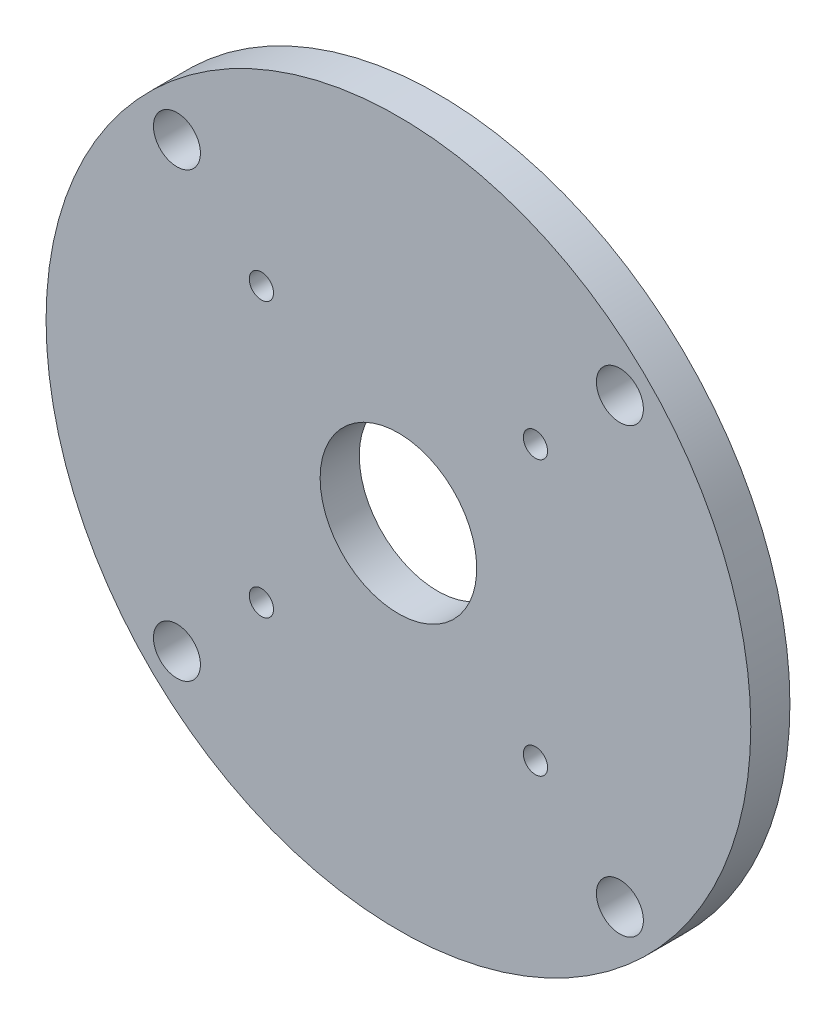
SolidWorks part; units mm, degrees
material "AISI 4130 Steel, normalized at 870C"
ref_plane "Front Plane" through (0, 0, 0) normal (0, 0, 1) x (1, 0, 0)
ref_plane "Top Plane" through (0, 0, 0) normal (0, 1, 0) x (1, 0, 0)
ref_plane "Right Plane" through (0, 0, 0) normal (1, 0, 0) x (0, 0, -1)
sketch "Sketch1" plane through (0, 0, 0) normal (0, 0, 1) x (1, 0, 0)
  line L1 (35.921, -35.921) -> (-35.921, -35.921) construction
  line L2 (35.921, -35.921) -> (35.921, 35.921) construction
  line L3 (35.921, 35.921) -> (-35.921, 35.921) construction
  line L4 (-35.921, -35.921) -> (-35.921, 35.921) construction
  line L5 (35.921, -35.921) -> (-35.921, 35.921) construction
  line L6 (35.921, 35.921) -> (-35.921, -35.921) construction
  circle A0 centre (0, 0) radius 50.8 construction
  circle A1 centre (-35.921, 35.921) radius 3.81
  circle A2 centre (35.921, 35.921) radius 3.81
  circle A3 centre (35.921, -35.921) radius 3.81
  circle A4 centre (-35.921, -35.921) radius 3.81
  point P17 (0, 0)
  dimension "D1" = 101.6
  dimension "D2" = 7.62
sketch "Sketch3" plane through (0, 0, 0) normal (0, 0, 1) x (1, 0, 0)
  line L0 (35.921, 35.921) -> (-35.921, -35.921) construction
  circle A0 centre (0, 0) radius 57.15
  dimension "D1" = 114.3
extrude "Boss-Extrude2" add sketch "Sketch3" along normal blind 6.35
sketch "Sketch4" plane through (0, 0, 0) normal (0, 0, -1) x (-1, 0, 0)
  circle A0 centre (-35.921, 35.921) radius 3.81
  circle A1 centre (35.921, 35.921) radius 3.81
  circle A2 centre (35.921, -35.921) radius 3.81
  circle A3 centre (-35.921, -35.921) radius 3.81
  circle A4 centre (0, 0) radius 12.7
  dimension "D1" = 25.4
extrude "Cut-Extrude1" cut sketch "Sketch4" against normal blind 6.35
sketch "Sketch5" plane through (0, 0, 6.35) normal (0, 0, 1) x (1, 0, 0)
  line L1 (22.225, -22.225) -> (-22.225, -22.225) construction
  line L2 (22.225, -22.225) -> (22.225, 22.225) construction
  line L3 (22.225, 22.225) -> (-22.225, 22.225) construction
  line L4 (-22.225, -22.225) -> (-22.225, 22.225) construction
  line L5 (22.225, -22.225) -> (-22.225, 22.225) construction
  line L6 (22.225, 22.225) -> (-22.225, -22.225) construction
  circle A0 centre (-22.225, 22.225) radius 1.9685
  circle A1 centre (22.225, 22.225) radius 1.9685
  circle A2 centre (22.225, -22.225) radius 1.9685
  circle A3 centre (-22.225, -22.225) radius 1.9685
  point P0 (0, 0)
  dimension "D3" = 3.937
  dimension "D4" = 3.937
  dimension "D5" = 3.937
  dimension "D6" = 3.937
  dimension "D1" = 44.45
  dimension "D2" = 44.45
extrude "Cut-Extrude2" cut sketch "Sketch5" against normal blind 6.35
